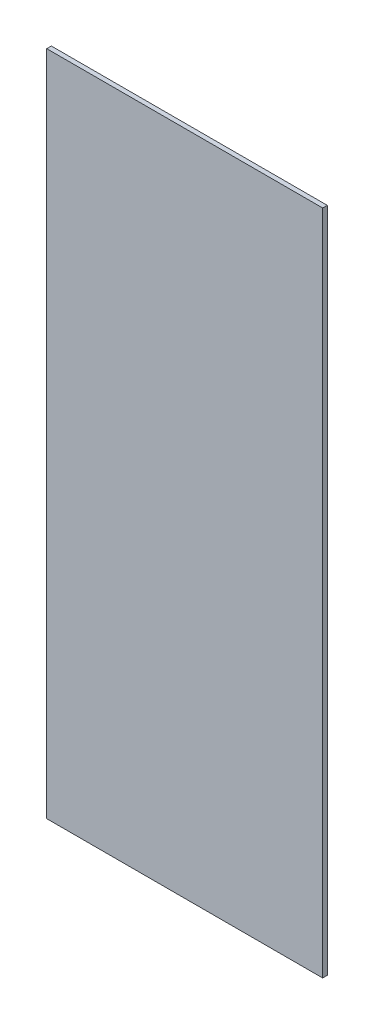
SolidWorks part; units mm, degrees
ref_plane "Front Plane" through (0, 0, 0) normal (0, 0, 1) x (1, 0, 0)
ref_plane "Top Plane" through (0, 0, 0) normal (0, 1, 0) x (1, 0, 0)
ref_plane "Right Plane" through (0, 0, 0) normal (1, 0, 0) x (0, 0, -1)
sketch "Sketch1" plane through (0, 0, 0) normal (0, 0, 1) x (1, 0, 0)
  line L1 (-60, 145) -> (60, 145)
  line L2 (-60, 145) -> (-60, -145)
  line L3 (-60, -145) -> (60, -145)
  line L4 (60, 145) -> (60, -145)
  line L5 (-60, 145) -> (60, -145) construction
  line L6 (-60, -145) -> (60, 145) construction
  point P0 (0, 0)
  point P5 (0, 0)
  dimension "D1" = 120
  dimension "D2" = 290
extrude "Boss-Extrude1" add sketch "Sketch1" along normal blind 2
